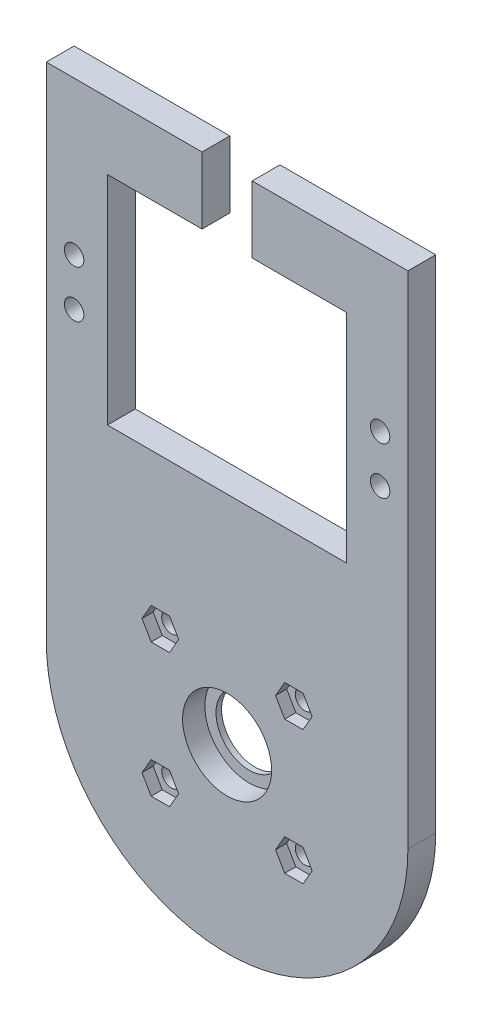
SolidWorks part; units mm, degrees
ref_plane "Front Plane" through (0, 0, 0) normal (0, 0, 1) x (1, 0, 0)
ref_plane "Top Plane" through (0, 0, 0) normal (0, 1, 0) x (1, 0, 0)
ref_plane "Right Plane" through (0, 0, 0) normal (1, 0, 0) x (0, 0, -1)
sketch "Sketch1" plane through (0, 0, 0) normal (0, 0, 1) x (1, 0, 0)
  line L2 (-32.5, 0) -> (-32.5, 90)
  line L3 (-32.5, 90) -> (32.5, 90)
  line L4 (32.5, 0) -> (32.5, 90)
  arc A0 (-32.5, 0) -> (32.5, 0) centre (0, 0) ccw
  dimension "D1" = 65
  dimension "D2" = 90
extrude "Boss-Extrude1" add sketch "Sketch1" along normal blind 5
sketch "Sketch2" plane through (0, 0, 5) normal (0, 0, 1) x (1, 0, 0)
  circle A0 centre (0, 0) radius 6
  dimension "D1" = 12
extrude "Cut-Extrude1" cut sketch "Sketch2" against normal through all
sketch "Sketch3" plane through (0, 0, 5) normal (0, 0, 1) x (1, 0, 0)
  circle A0 centre (0, 0) radius 8
  dimension "D1" = 16
extrude "Cut-Extrude2" cut sketch "Sketch3" against normal blind 4
sketch "Sketch4" plane through (0, 0, 5) normal (0, 0, 1) x (1, 0, 0)
  line L0 (-4.4468, 0) -> (0, 0) construction
  line L1 (0, 0) -> (0, 5.0638) construction
  circle A0 centre (-12, 12) radius 1.75
  circle A1 centre (12, 12) radius 1.75
  circle A2 centre (12, -12) radius 1.75
  circle A3 centre (-12, -12) radius 1.75
  dimension "D1" = 3.5
  dimension "D2" = 12
  dimension "D3" = 12
extrude "Cut-Extrude3" cut sketch "Sketch4" against normal through all
sketch "Sketch5" plane through (0, 0, 5) normal (0, 0, 1) x (1, 0, 0)
  line L0 (32.5, 90) -> (-32.5, 90) construction
  line L1 (-21.5, 78) -> (-4.5041, 78)
  line L2 (-21.5, 78) -> (-21.5, 39)
  line L3 (-21.5, 39) -> (21.5, 39)
  line L4 (21.5, 78) -> (21.5, 39)
  line L5 (-21.5, 78) -> (21.5, 39) construction
  line L6 (-21.5, 39) -> (21.5, 78) construction
  line L7 (4.5041, 78) -> (21.5, 78)
  line L8 (-4.5041, 90) -> (4.5041, 90)
  line L9 (-4.5041, 90) -> (-4.5041, 78)
  line L11 (4.5041, 90) -> (4.5041, 78)
  line L12 (-4.5041, 90) -> (4.5041, 78) construction
  line L13 (-4.5041, 78) -> (4.5041, 90) construction
  point P0 (0, 58.5)
  point P8 (0, 84)
  dimension "D1" = 39
  dimension "D2" = 43
  dimension "D3" = 12
  dimension "D4" = 12
extrude "Cut-Extrude4" cut sketch "Sketch5" against normal through all
sketch "Sketch7" plane through (0, 0, 5) normal (0, 0, 1) x (1, 0, 0)
  line L0 (3.0888, 0) -> (0, 0) construction
  line L1 (-8.7091, 12) -> (-10.3546, 14.85)
  line L2 (-10.3546, 14.85) -> (-13.6454, 14.85)
  line L3 (-13.6454, 14.85) -> (-15.2909, 12)
  line L4 (-15.2909, 12) -> (-13.6454, 9.15)
  line L5 (-13.6454, 9.15) -> (-10.3546, 9.15)
  line L6 (-10.3546, 9.15) -> (-8.7091, 12)
  line L7 (0, 0) -> (0, 3.9343) construction
  line L8 (10.3546, 9.15) -> (8.7091, 12)
  line L9 (13.6454, 9.15) -> (10.3546, 9.15)
  line L10 (15.2909, 12) -> (13.6454, 9.15)
  line L11 (13.6454, 14.85) -> (15.2909, 12)
  line L12 (10.3546, 14.85) -> (13.6454, 14.85)
  line L13 (8.7091, 12) -> (10.3546, 14.85)
  line L14 (8.7091, -12) -> (10.3546, -14.85)
  line L15 (10.3546, -14.85) -> (13.6454, -14.85)
  line L16 (13.6454, -14.85) -> (15.2909, -12)
  line L17 (15.2909, -12) -> (13.6454, -9.15)
  line L18 (13.6454, -9.15) -> (10.3546, -9.15)
  line L19 (10.3546, -9.15) -> (8.7091, -12)
  line L20 (-10.3546, -9.15) -> (-8.7091, -12)
  line L21 (-13.6454, -9.15) -> (-10.3546, -9.15)
  line L22 (-15.2909, -12) -> (-13.6454, -9.15)
  line L23 (-13.6454, -14.85) -> (-15.2909, -12)
  line L24 (-10.3546, -14.85) -> (-13.6454, -14.85)
  line L25 (-8.7091, -12) -> (-10.3546, -14.85)
  circle A0 centre (-12, 12) radius 2.85 construction
  circle A1 centre (12, 12) radius 2.85 construction
  circle A2 centre (12, -12) radius 2.85 construction
  circle A3 centre (-12, -12) radius 2.85 construction
  dimension "D1" = 5.7
extrude "Cut-Extrude6" cut sketch "Sketch7" against normal blind 2
sketch "Sketch8" plane through (0, 0, 0) normal (0, 0, -1) x (-1, 0, 0)
  line L0 (-32.5, 90) -> (-4.5041, 90) construction
  line L1 (-32.5, 0) -> (-32.5, 90) construction
  line L3 (0, 56.8218) -> (0, 47.6677) construction
  circle A0 centre (-27.5, 62.5) radius 1.75
  circle A1 centre (-27.5, 54) radius 1.75
  circle A2 centre (27.5, 54) radius 1.75
  circle A3 centre (27.5, 62.5) radius 1.75
  dimension "D1" = 3.5
  dimension "D4" = 3.5
  dimension "D2" = 27.5
  dimension "D3" = 5
  dimension "D5" = 8.5
extrude "Cut-Extrude7" cut sketch "Sketch8" against normal through all
